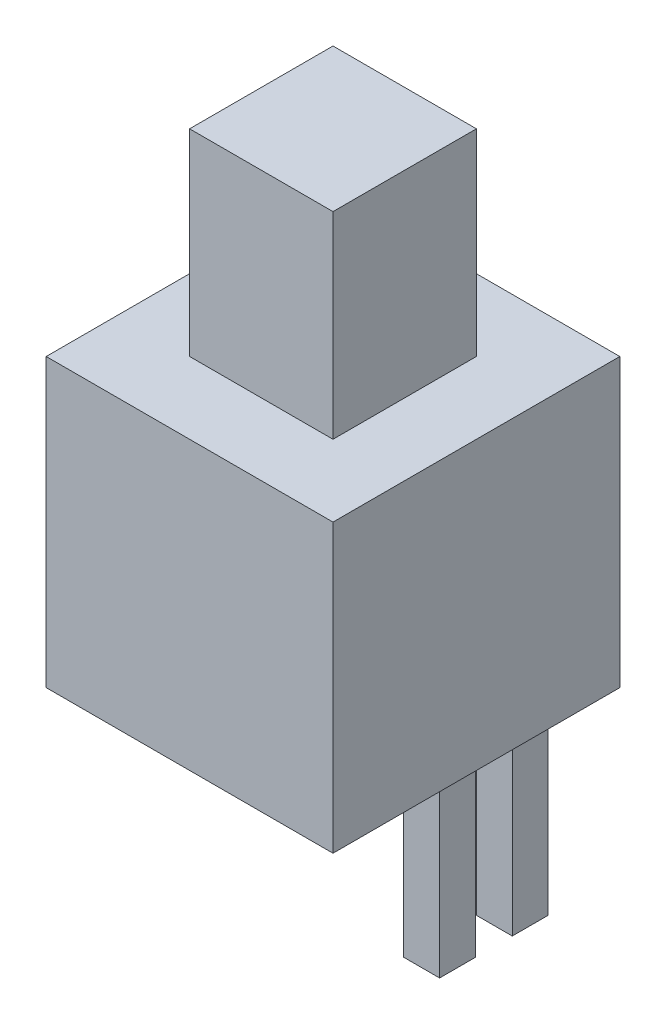
SolidWorks part; units mm, degrees
ref_plane "Front Plane" through (0, 0, 0) normal (0, 0, 1) x (1, 0, 0)
ref_plane "Top Plane" through (0, 0, 0) normal (0, 1, 0) x (1, 0, 0)
ref_plane "Right Plane" through (0, 0, 0) normal (1, 0, 0) x (0, 0, -1)
sketch "Sketch1" plane through (0, 0, 0) normal (0, 1, 0) x (1, 0, 0)
  line L1 (-4, -4) -> (4, -4)
  line L2 (-4, -4) -> (-4, 4)
  line L3 (-4, 4) -> (4, 4)
  line L4 (4, -4) -> (4, 4)
  line L5 (-4, -4) -> (4, 4) construction
  line L6 (-4, 4) -> (4, -4) construction
  point P0 (0, 0)
  dimension "D1" = 8
  dimension "D2" = 8
extrude "Boss-Extrude1" add sketch "Sketch1" along normal blind 8
sketch "Sketch2" plane through (0, 8, 0) normal (0, 1, 0) x (1, 0, 0)
  line L1 (-2, -2) -> (2, -2)
  line L2 (-2, -2) -> (-2, 2)
  line L3 (-2, 2) -> (2, 2)
  line L4 (2, -2) -> (2, 2)
  line L5 (-2, -2) -> (2, 2) construction
  line L6 (-2, 2) -> (2, -2) construction
  point P0 (0, 0)
  dimension "D1" = 4
  dimension "D2" = 4
extrude "Boss-Extrude2" add sketch "Sketch2" along normal blind 5.5
sketch "Sketch3" plane through (0, 0, 0) normal (0, -1, 0) x (1, 0, 0)
  line L0 (4, -4) -> (-4, -4) construction
  line L1 (2, -2) -> (3, -2)
  line L2 (2, -2) -> (2, -3)
  line L3 (2, -3) -> (3, -3)
  line L4 (3, -2) -> (3, -3)
  line L5 (2, -2) -> (3, -3) construction
  line L6 (2, -3) -> (3, -2) construction
  line L7 (2, 0.0267) -> (3, 0.0267)
  line L8 (2, 0.0267) -> (2, -0.9733)
  line L9 (2, -0.9733) -> (3, -0.9733)
  line L10 (3, 0.0267) -> (3, -0.9733)
  line L11 (2, 0.0267) -> (3, -0.9733) construction
  line L12 (2, -0.9733) -> (3, 0.0267) construction
  line L13 (4, 4) -> (4, -4) construction
  point P0 (2.5, -2.5)
  point P5 (2.5, -0.4733)
  dimension "D1" = 1
  dimension "D2" = 1
  dimension "D3" = 1
  dimension "D4" = 1
  dimension "D5" = 2.0267
  dimension "D6" = 1
  dimension "D7" = 1
extrude "Boss-Extrude3" add sketch "Sketch3" along normal blind 5.5
